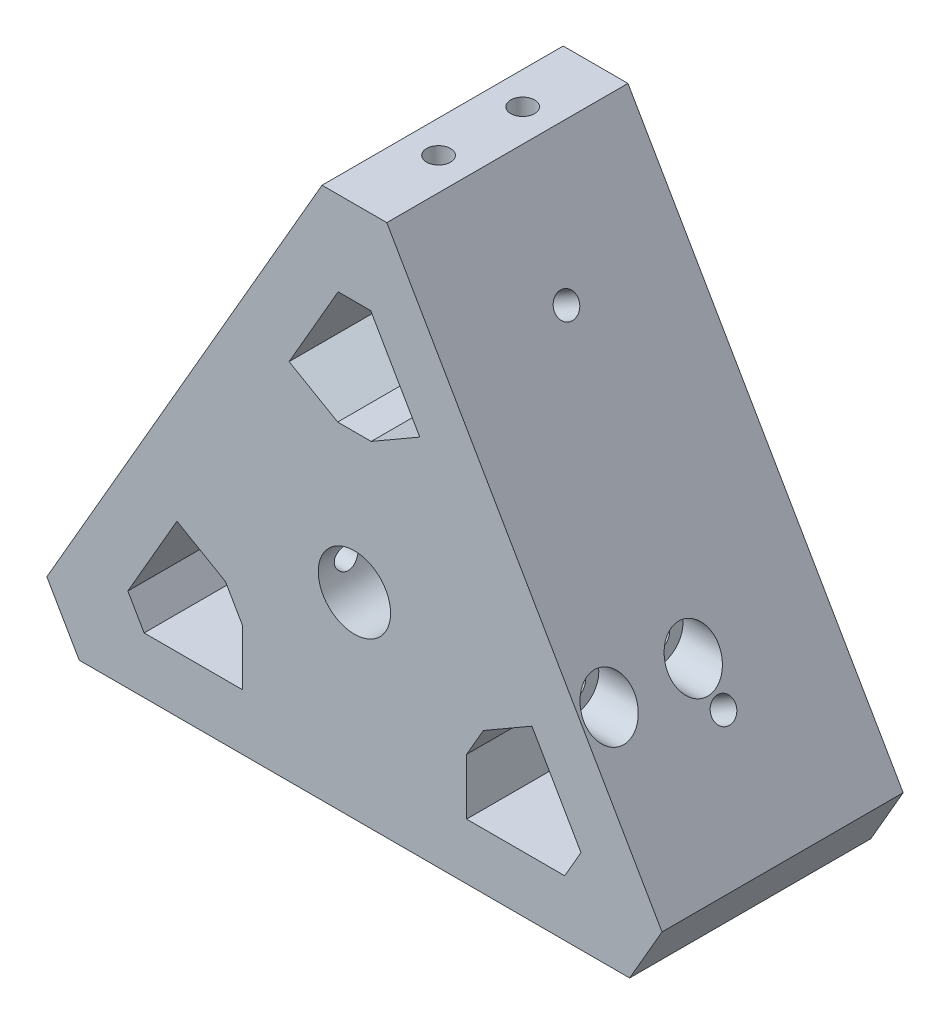
SolidWorks part; units mm, degrees
material "PLA"
ref_plane "前视基准面" through (0, 0, 0) normal (0, 0, 1) x (1, 0, 0)
ref_plane "上视基准面" through (0, 0, 0) normal (0, 1, 0) x (1, 0, 0)
ref_plane "右视基准面" through (0, 0, 0) normal (1, 0, 0) x (0, 0, -1)
other "Configuration Table"
sketch "草图1" plane through (0, 0, 0) normal (0, 0, 1) x (1, 0, 0)
  line L0 (0, 70) -> (-60.6218, -35)
  line L5 (-60.6218, -35) -> (60.6218, -35)
  line L6 (60.6218, -35) -> (0, 70)
  line L11 (0, 0) -> (0, 42.5867) construction
  line L13 (0, 0) -> (0, -35) construction
  line L14 (0, 0) -> (30.3109, 17.5) construction
  line L15 (-5.7735, 60) -> (5.7735, 60)
  line L16 (54.8483, -25) -> (49.0748, -35)
  line L17 (-49.0748, -35) -> (-54.8483, -25)
  circle A1 centre (0, 0) radius 6.45
  point P18 (0, 0)
  dimension "D5" = 3
  dimension "D1" = 12.9
  dimension "D2" = 60
  dimension "D3" = 35
  dimension "D4" = 10
extrude "凸台-拉伸1" add sketch "草图1" along normal blind 43 contours L17 L5 L16 L6 L15 L0 A1
sketch "草图2" plane through (0, 0, 43) normal (0, 0, 1) x (1, 0, 0)
  line L0 (-2.9006, 44.976) -> (5.7596, 39.976)
  line L1 (5.7596, 39.976) -> (-31.7404, -24.976)
  line L2 (-5.7735, 60) -> (-54.8483, -25) construction
  line L3 (0, 0) -> (-68.0781, 39.3049) construction
  line L4 (-40.4006, -19.976) -> (-31.7404, -24.976)
  line L5 (-40.4006, -19.976) -> (-2.9006, 44.976)
  line L6 (40.4006, -19.976) -> (31.7404, -24.976)
  line L7 (31.7404, -24.976) -> (-5.7596, 39.976)
  line L8 (2.9006, 44.976) -> (-5.7596, 39.976)
  line L9 (2.9006, 44.976) -> (40.4006, -19.976)
  line L10 (-37.5, -25) -> (-37.5, -15)
  line L11 (-37.5, -15) -> (37.5, -15)
  line L12 (37.5, -25) -> (37.5, -15)
  line L13 (37.5, -25) -> (-37.5, -25)
  line L14 (-2.9904, 24.8205) -> (-11.6506, 29.8205)
  line L15 (-22.9904, -9.8205) -> (-31.6506, -4.8205)
  line L16 (22.9904, -9.8205) -> (31.6506, -4.8205)
  line L17 (2.9904, 24.8205) -> (11.6506, 29.8205)
  line L18 (-20, -15) -> (-20, -25)
  line L19 (20, -15) -> (20, -25)
  line L20 (-2.9006, 44.976) -> (2.9006, 44.976)
  line L21 (-40.4006, -19.976) -> (-37.5, -25)
  line L22 (40.4006, -19.976) -> (37.5, -25)
  line L23 (-22.9904, -9.8205) -> (-20, -15)
  line L24 (22.9904, -9.8205) -> (20, -15)
  line L25 (2.9904, 24.8205) -> (-2.9904, 24.8205)
  point P19 (0, 0)
  point P33 (0, 0)
  dimension "D1" = 75
  dimension "D2" = 10
  dimension "D3" = 10
  dimension "D5" = 40
  dimension "D4" = 3
  dimension "D6" = 3
extrude "切除-拉伸3" cut sketch "草图2" against normal through all contours L0 L8 L7 L1 | L14 L1 L7 L8 L0 L5 | L7 L17 L9 L8 L0 L1 | L1 L15 L5 L4 L10 L11 | L11 L10 L4 L1 | L18 L11 L1 L4 L10 L13 | L11 L19 L13 L12 L6 L7 | L6 L12 L11 L7 | L16 L7 L11 L12 L6 L9 | L20 L0 L8 | L4 L21 L10 | L22 L6 L12 | L7 L24 L11 | L23 L1 L11 | L25 L7 L1
sketch "草图3" plane through (-30.3109, 17.5, 0) normal (-0.866, 0.5, 0) x (0, 0, 1)
  line L0 (0, 0) -> (67.8776, 0) construction
  line L1 (0, 49.0748) -> (0, -49.0748) construction
  line L2 (43, 54.8483) -> (0, 54.8483) construction
  circle A0 centre (21.5, 28) radius 2.125
  circle A2 centre (21.5, -28) radius 2.125
  point P10 (21.5, 54.8483)
  dimension "D1" = 56
  dimension "D2" = 4.25
extrude "切除-拉伸4" cut sketch "草图3" against normal blind 15
pattern_circular "阵列(圆周)1" count 3 over 360 about axis through (0, 0, 43) along (0, 0, -1) of "切除-拉伸4"
sketch "草图4" plane through (0, -35, 0) normal (0, -1, 0) x (1, 0, 0)
  line L0 (-49.0748, 0) -> (49.0748, 0) construction
  circle A0 centre (0, 13) radius 2.125
  circle A1 centre (0, 28) radius 2.125
  dimension "D1" = 13
  dimension "D2" = 15
  dimension "D3" = 4.25
extrude "切除-拉伸5" cut sketch "草图4" against normal through all
ref_plane "基准面1" through (49.0748, 0, 0) normal (-1, 0, 0) x (0, 0, -1)
sketch "草图6" plane through (49.0748, 0, 0) normal (-1, 0, 0) x (0, 0, -1)
  line L5 (0, 25) -> (0, -60) construction
  line L6 (-21.5, 35) -> (-21.5, -35) construction
  line L7 (-43, 35) -> (0, 35) construction
  circle A0 centre (-23, 0) radius 2.15
  circle A1 centre (-38, 0) radius 2.15
  point P7 (-21.5, 0)
  dimension "D1" = 15
  dimension "D2" = 70
  dimension "D3" = 4.3
  dimension "D4" = 23
extrude "切除-拉伸7" cut sketch "草图6" along normal through all
sketch "草图7" plane through (49.0748, 0, 0) normal (-1, 0, 0) x (0, 0, -1)
  circle A0 centre (-38, 0) radius 4.5
  circle A1 centre (-23, 0) radius 4.5
  dimension "D1" = 9
  dimension "D2" = 9
extrude "切除-拉伸8" cut sketch "草图7" along normal blind 15
